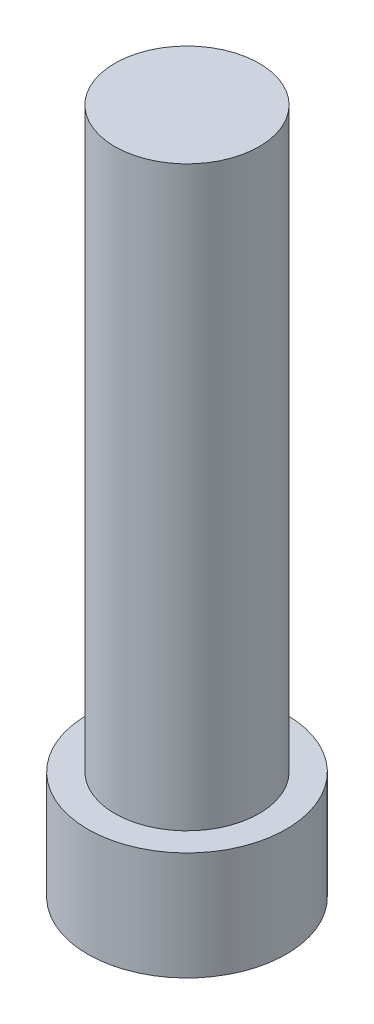
SolidWorks part; units mm, degrees
ref_plane "前视基准面" through (0, 0, 0) normal (0, 0, 1) x (1, 0, 0)
ref_plane "上视基准面" through (0, 0, 0) normal (0, 1, 0) x (1, 0, 0)
ref_plane "右视基准面" through (0, 0, 0) normal (1, 0, 0) x (0, 0, -1)
other "Configuration Table"
sketch "草图1" plane through (0, 0, 0) normal (0, 1, 0) x (1, 0, 0)
  circle A0 centre (0, 0) radius 2.75
  dimension "D1" = 5.5
extrude "凸台-拉伸1" add sketch "草图1" along normal blind 3
sketch "草图2" plane through (0, 3, 0) normal (0, 1, 0) x (1, 0, 0)
  circle A0 centre (0, 0) radius 2
  dimension "D1" = 4
extrude "凸台-拉伸2" add sketch "草图2" along normal blind 16
cosmetic thread "装饰螺纹线1"
sketch "草图3" plane through (0, 0, 0) normal (0, -1, 0) x (1, 0, 0)
  line L1 (1.0917, -0.9442) -> (1.3636, 0.4733)
  line L2 (1.3636, 0.4733) -> (0.2719, 1.4175)
  line L3 (0.2719, 1.4175) -> (-1.0917, 0.9442)
  line L4 (-1.0917, 0.9442) -> (-1.3636, -0.4733)
  line L5 (-1.3636, -0.4733) -> (-0.2719, -1.4175)
  line L6 (-0.2719, -1.4175) -> (1.0917, -0.9442)
  circle A0 centre (0, 0) radius 1.25 construction
  dimension "D1" = 2.5
extrude "切除-拉伸1" cut sketch "草图3" against normal blind 1.5
